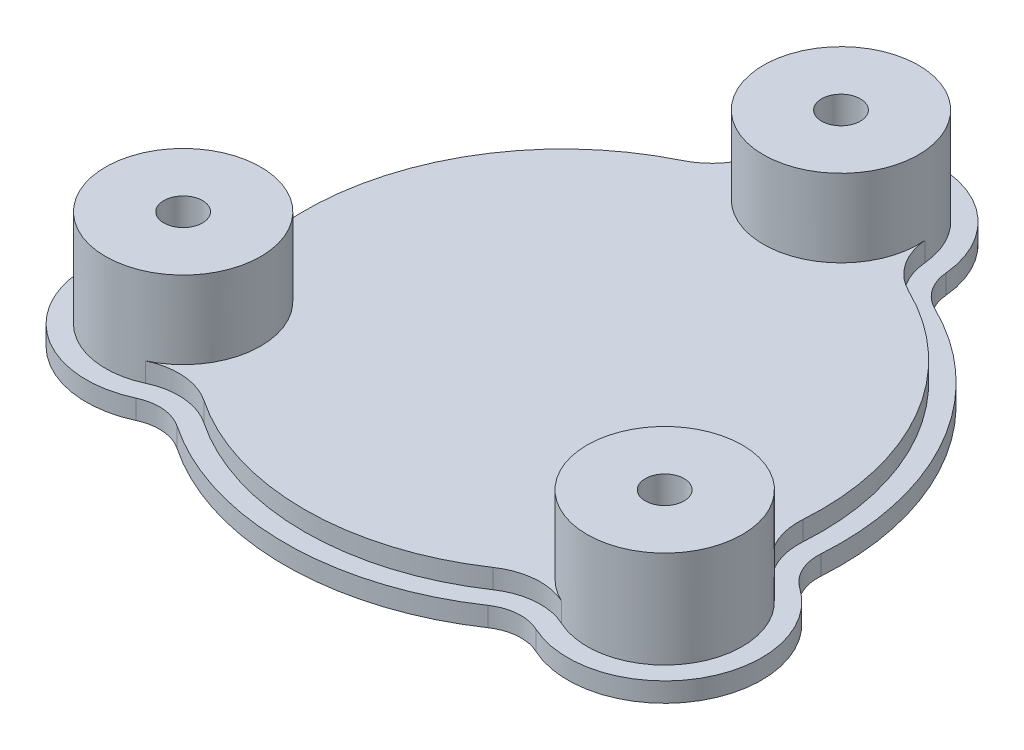
SolidWorks part; units mm, degrees
ref_plane "Płaszczyzna przednia" through (0, 0, 0) normal (0, 0, 1) x (1, 0, 0)
ref_plane "Płaszczyzna górna" through (0, 0, 0) normal (0, 1, 0) x (1, 0, 0)
ref_plane "Płaszczyzna prawa" through (0, 0, 0) normal (1, 0, 0) x (0, 0, -1)
sketch "Szkic1" plane through (0, 0, 0) normal (0, 1, 0) x (1, 0, 0)
  line L0 (0, 0) -> (0, 43) construction
  arc A0 (-39.8693, -16.1072) -> (-33.8839, -26.4742) centre (0, 0) ccw
  circle A1 centre (0, 43) radius 6
  circle A2 centre (37.2391, -21.5) radius 6
  circle A3 centre (-37.2391, -21.5) radius 6
  circle A4 centre (0, 43) radius 15
  circle A5 centre (37.2391, -21.5) radius 15
  circle A6 centre (-37.2391, -21.5) radius 15
  arc A7 (-30.915, -35.1017) -> (-24.0488, -35.6462) centre (-27.9637, -41.4491) cw
  arc A8 (-44.9043, -8.6064) -> (-42.7765, -4.3781) centre (-47.1518, -4.8259) ccw
  arc A9 (-18.8462, 38.65) -> (-14.9415, 44.324) centre (-21.9141, 44.9419) ccw
  arc A10 (14.9415, 44.324) -> (18.8462, 38.65) centre (21.9141, 44.9419) ccw
  arc A11 (42.895, -3.0038) -> (45.8564, -9.2223) centre (49.8779, -3.4927) ccw
  arc A12 (24.0488, -35.6462) -> (30.915, -35.1017) centre (27.9637, -41.4491) cw
  arc A13 (-27.5883, -32.9831) -> (27.5883, -32.9831) centre (0, 0) ccw
  arc A14 (33.8839, -26.4742) -> (39.8693, -16.1072) centre (0, 0) ccw
  arc A15 (42.3584, -7.4006) -> (14.7701, 40.3837) centre (0, 0) ccw
  arc A16 (5.9854, 42.5814) -> (-5.9854, 42.5814) centre (0, 0) ccw
  arc A17 (-14.7701, 40.3837) -> (-42.3584, -7.4006) centre (0, 0) ccw
  point P12 (0, 0)
  point P17 (0, 0)
  dimension "D1" = 86
  dimension "D2" = 12
  dimension "D4" = 30
  dimension "D6" = 7
  dimension "D7" = 7
  dimension "D8" = 7
  dimension "D9" = 7
  dimension "D10" = 7
  dimension "D11" = 4.3981
  dimension "D3" = 3
  dimension "D5" = 3
extrude "Dodanie-wyciągnięcie3" add sketch "Szkic1" along normal blind 3
sketch "Szkic2" plane through (0, 3, 0) normal (0, 1, 0) x (1, 0, 0)
  circle A12 centre (37.2391, -21.5) radius 6 construction
  circle A13 centre (0, 43) radius 6 construction
  circle A14 centre (-37.2391, -21.5) radius 6 construction
  circle A15 centre (37.2391, -21.5) radius 6
  circle A16 centre (0, 43) radius 6
  circle A17 centre (-37.2391, -21.5) radius 6
  arc A24 (32.1798, -32.3813) -> (22.371, -33.1593) centre (27.9637, -41.4491) ccw
  arc A25 (32.1798, -32.3813) -> (44.133, -11.6779) centre (37.2391, -21.5) ccw
  arc A26 (39.9023, -2.7942) -> (44.133, -11.6779) centre (49.8779, -3.4927) ccw
  arc A27 (39.9023, -2.7942) -> (17.5313, 35.9535) centre (0, 0) ccw
  arc A28 (11.9532, 44.0592) -> (17.5313, 35.9535) centre (21.9141, 44.9419) ccw
  arc A29 (11.9532, 44.0592) -> (-11.9532, 44.0592) centre (0, 43) ccw
  arc A30 (-17.5313, 35.9535) -> (-11.9532, 44.0592) centre (-21.9141, 44.9419) ccw
  arc A31 (-17.5313, 35.9535) -> (-39.7921, -4.0727) centre (0, 0) ccw
  arc A32 (-43.3712, -11.1851) -> (-39.7921, -4.0727) centre (-47.1518, -4.8259) ccw
  arc A33 (-43.3712, -11.1851) -> (-32.1798, -32.3813) centre (-37.2391, -21.5) ccw
  arc A34 (-22.371, -33.1593) -> (-32.1798, -32.3813) centre (-27.9637, -41.4491) ccw
  arc A35 (-22.371, -33.1593) -> (22.371, -33.1593) centre (0, 0) ccw
  arc A36 (32.1798, -32.3813) -> (22.371, -33.1593) centre (27.9637, -41.4491) ccw
  arc A37 (32.1798, -32.3813) -> (44.133, -11.6779) centre (37.2391, -21.5) ccw
  arc A38 (39.9023, -2.7942) -> (44.133, -11.6779) centre (49.8779, -3.4927) ccw
  arc A39 (39.9023, -2.7942) -> (17.5313, 35.9535) centre (0, 0) ccw
  arc A40 (11.9532, 44.0592) -> (17.5313, 35.9535) centre (21.9141, 44.9419) ccw
  arc A41 (11.9532, 44.0592) -> (-11.9532, 44.0592) centre (0, 43) ccw
  arc A42 (-17.5313, 35.9535) -> (-11.9532, 44.0592) centre (-21.9141, 44.9419) ccw
  arc A43 (-17.5313, 35.9535) -> (-39.7921, -4.0727) centre (0, 0) ccw
  arc A44 (-43.3712, -11.1851) -> (-39.7921, -4.0727) centre (-47.1518, -4.8259) ccw
  arc A45 (-43.3712, -11.1851) -> (-32.1798, -32.3813) centre (-37.2391, -21.5) ccw
  arc A46 (-22.371, -33.1593) -> (-32.1798, -32.3813) centre (-27.9637, -41.4491) ccw
  arc A47 (-22.371, -33.1593) -> (22.371, -33.1593) centre (0, 0) ccw
  dimension "D1" = 3
extrude "Dodanie-wyciągnięcie5" add sketch "Szkic2" along normal blind 3
sketch "Szkic3" plane through (0, 6, 0) normal (0, 1, 0) x (1, 0, 0)
  circle A6 centre (0, 43) radius 12
  circle A7 centre (37.2391, -21.5) radius 12
  circle A8 centre (-37.2391, -21.5) radius 12
  point P3 (37.2391, -21.5)
  point P11 (37.2391, -21.5)
  point P12 (0, 0)
  point P17 (0, 0)
  dimension "D1" = 24
  dimension "D3" = 6.8939
  dimension "D4" = 44.133
  dimension "D5" = 11.6779
  dimension "D2" = 3
extrude "Dodanie-wyciągnięcie7" add sketch "Szkic3" along normal offset from surface (12 mm away) 18 contours A6 | A8 | A7 up to face at (-0.0233, 0, 0.0337)
sketch "Szkic4" plane through (0, 18, 0) normal (0, 1, 0) x (1, 0, 0)
  circle A1 centre (0, 43) radius 12 construction
  circle A2 centre (0, 43) radius 12
  circle A3 centre (0, 43) radius 3
  circle A4 centre (37.2391, -21.5) radius 3
  circle A5 centre (-37.2391, -21.5) radius 3
  point P4 (46.1085, -26.3963)
  point P5 (0, 0)
  point P6 (0, 0)
  point P11 (0, 0)
  point P12 (0, 0)
  dimension "D1" = 6
  dimension "D2" = 3
extrude "Wytnij-wyciągnięcie1" cut sketch "Szkic4" against normal blind 6 contours A3 | A4 | A5
sketch "Szkic5" plane through (0, 6, 0) normal (0, -1, 0) x (1, 0, 0)
  circle A0 centre (37.2391, 21.5) radius 6 construction
  circle A1 centre (0, -43) radius 6 construction
  circle A2 centre (-37.2391, 21.5) radius 6 construction
  circle A3 centre (37.2391, 21.5) radius 6
  circle A4 centre (0, -43) radius 6
  circle A5 centre (-37.2391, 21.5) radius 6
extrude "Wytnij-wyciągnięcie2" cut sketch "Szkic5" against normal blind 6
